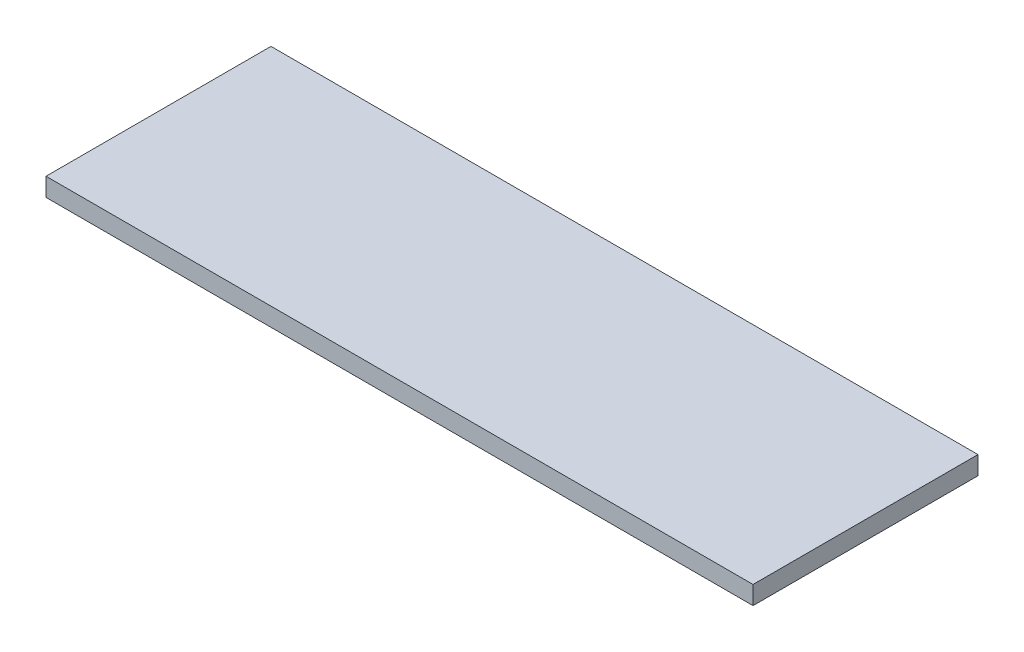
SolidWorks part; units mm, degrees
ref_plane "Front Plane" through (0, 0, 0) normal (0, 0, 1) x (1, 0, 0)
ref_plane "Top Plane" through (0, 0, 0) normal (0, 1, 0) x (1, 0, 0)
ref_plane "Right Plane" through (0, 0, 0) normal (1, 0, 0) x (0, 0, -1)
sketch "Sketch1" plane through (0, 0, 0) normal (0, 1, 0) x (1, 0, 0)
  line L0 (-53.1058, 0) -> (56.6058, 0) construction
  line L1 (0, 28.5385) -> (0, -28.5385) construction
  line L3 (-38.5, 12.25) -> (38.5, 12.25)
  line L4 (-38.5, 12.25) -> (-38.5, -12.25)
  line L5 (-38.5, -12.25) -> (38.5, -12.25)
  line L6 (38.5, 12.25) -> (38.5, -12.25)
  dimension "D1" = 24.5
  dimension "D2" = 77
extrude "Boss-Extrude1" add sketch "Sketch1" along normal blind 2
